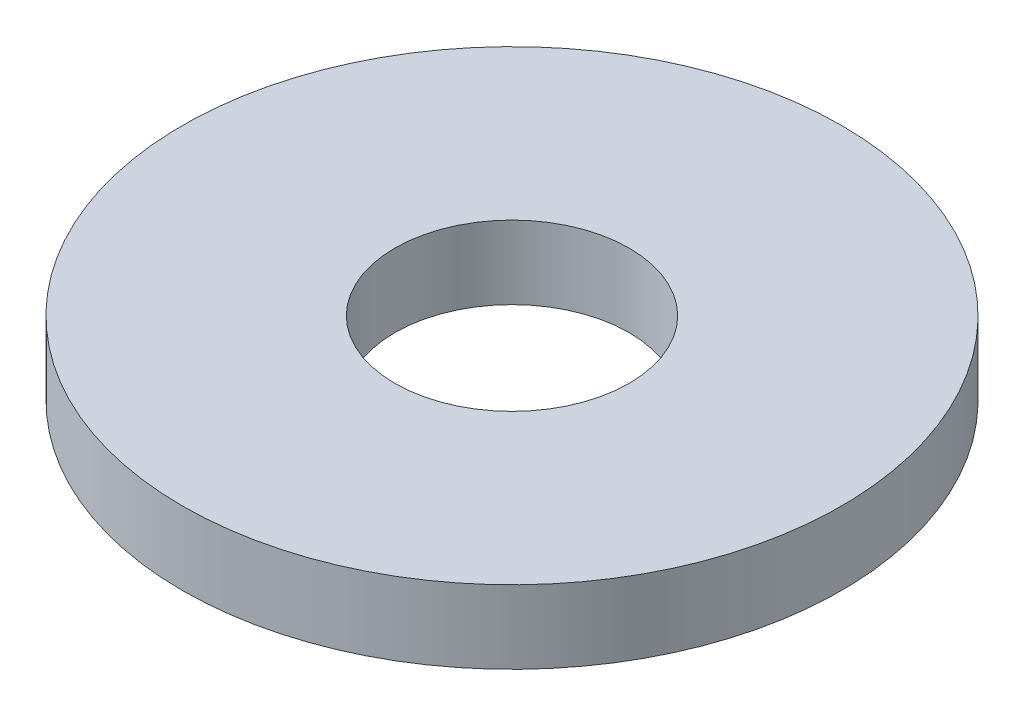
SolidWorks part; units mm, degrees
material "AISI 1020"
ref_plane "Front Plane" through (0, 0, 0) normal (0, 0, 1) x (1, 0, 0)
ref_plane "Top Plane" through (0, 0, 0) normal (0, 1, 0) x (1, 0, 0)
ref_plane "Right Plane" through (0, 0, 0) normal (1, 0, 0) x (0, 0, -1)
sketch "Sketch1" plane through (0, 0, 0) normal (0, 1, 0) x (1, 0, 0)
  circle A0 centre (0, 0) radius 1.6
  circle A1 centre (0, 0) radius 4.5
  dimension "D1" = 3.2
  dimension "D2" = 9
extrude "Boss-Extrude1" add sketch "Sketch1" along normal blind 1
